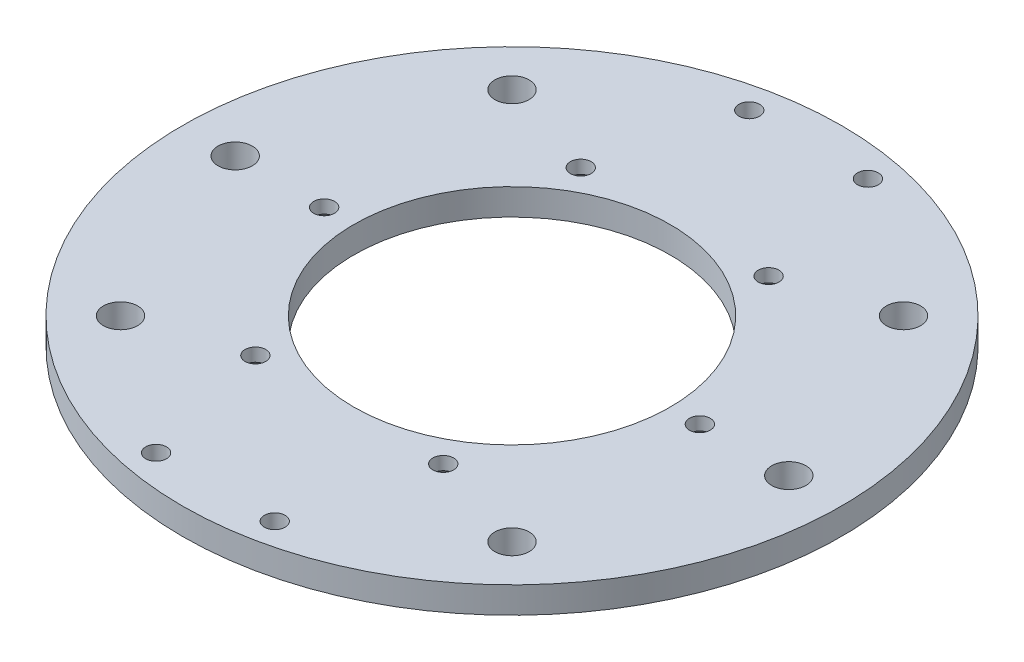
SolidWorks part; units mm, degrees
ref_plane "Спереди" through (0, 0, 0) normal (0, 0, 1) x (1, 0, 0)
ref_plane "Сверху" through (0, 0, 0) normal (0, 1, 0) x (1, 0, 0)
ref_plane "Справа" through (0, 0, 0) normal (1, 0, 0) x (0, 0, -1)
sketch "Эскиз1" plane through (0, 0, 0) normal (0, 1, 0) x (1, 0, 0)
  circle A0 centre (0, 0) radius 24
  circle A1 centre (0, 0) radius 50
  dimension "D1" = 48
  dimension "D2" = 100
extrude "Бобышка-Вытянуть1" add sketch "Эскиз1" along normal blind 4
hole_wizard "Сверло под метчик  спиральное M31" positions "Эскиз2" profile "Эскиз3" hole size "M3x0.5" standard "DIN"
sketch "Эскиз2" plane through (0, 4, 0) normal (0, 1, 0) x (1, 0, 0)
  point P0 (28.5, 0)
  dimension "D1" = 28.5
sketch "Эскиз3" plane through (28.5, 4, 0) normal (1, 0, 0) x (0, 0, 1)
  line L0 (0, 0) -> (0, 8.9464)
  line L1 (0, 8.9464) -> (1.575, 8)
  line L2 (1.575, 8) -> (1.575, 0)
  line L5 (1.575, 0) -> (0, 0)
  line L10 (0, 8.9464) -> (-1.575, 8) construction
  line L11 (0, -6.35) -> (0, 107.95) construction
  dimension "Диаметр отверстия" = 3.15
  dimension "Глубина отверстия" = 8
  dimension "Угол заточки сверла" = 118
pattern_circular "Круговой массив1" count 6 over 360 about axis through (0, 0, 0) along (0, 1, 0) of "Сверло под метчик  спиральное M31"
chamfer "Фаска1" distance 2 angle 45 6 edges at (-14.25, 0, 26.2567) (-28.5, 0, 1.575) (-14.25, 0, -23.1067) (14.25, 0, -23.1067) (28.5, 0, 1.575) (14.25, 0, 26.2567)
hole_wizard "Сверло под метчик  спиральное M32" positions "Эскиз4" profile "Эскиз5" hole size "M3x0.5" standard "DIN" end condition through all
sketch "Эскиз4" plane through (0, 0, 0) normal (0, -1, 0) x (-1, 0, 0)
  point P0 (-9, -45)
  dimension "D1" = 9
  dimension "D2" = 45
sketch "Эскиз5" plane through (9, 0, 45) normal (1, 0, 0) x (0, 0, -1)
  line L0 (0, 0) -> (0, 4)
  line L1 (0, 4) -> (1.575, 4)
  line L2 (1.575, 4) -> (1.575, 0)
  line L5 (1.575, 0) -> (0, 0)
  line L11 (0, -6.35) -> (0, 107.95) construction
  dimension "Диаметр сквозного отверстия" = 3.15
  dimension "Глубина сквозного отверстия" = 4
sketch "Эскиз6" plane through (0, 0, 0) normal (0, 1, 0) x (1, 0, 0)
  line L0 (0, 0) -> (0, 15.2777) construction
  line L1 (0, 0) -> (-12.2514, 0) construction
pattern_linear "Линейный массив1" count 2 spacing 18 along (-1, 0, 0) count 2 spacing 90 along (0, 0, -1) of "Сверло под метчик  спиральное M32"
hole_wizard "Сверло под метчик  спиральное M52" positions "Эскиз11" profile "Эскиз12" hole size "M5x0.8" standard "DIN" end condition through all
sketch "Эскиз11" plane through (0, 0, 0) normal (0, -1, 0) x (-1, 0, 0)
  point P0 (42, 0)
  point P2 (-42, 0)
  point P6 (0, 0)
  dimension "D1" = 42
  dimension "D2" = 42
sketch "Эскиз12" plane through (-42, 0, 0) normal (1, 0, 0) x (0, 0, -1)
  line L0 (0, 0) -> (0, 4)
  line L1 (0, 4) -> (2.6, 4)
  line L2 (2.6, 4) -> (2.6, 0)
  line L5 (2.6, 0) -> (0, 0)
  line L11 (0, -6.35) -> (0, 107.95) construction
  dimension "Диаметр сквозного отверстия" = 5.2
  dimension "Глубина сквозного отверстия" = 4
pattern_circular "Круговой массив3" count 2 every 45 about axis through (0, 0, 0) along (0, 1, 0) of "Сверло под метчик  спиральное M52"
